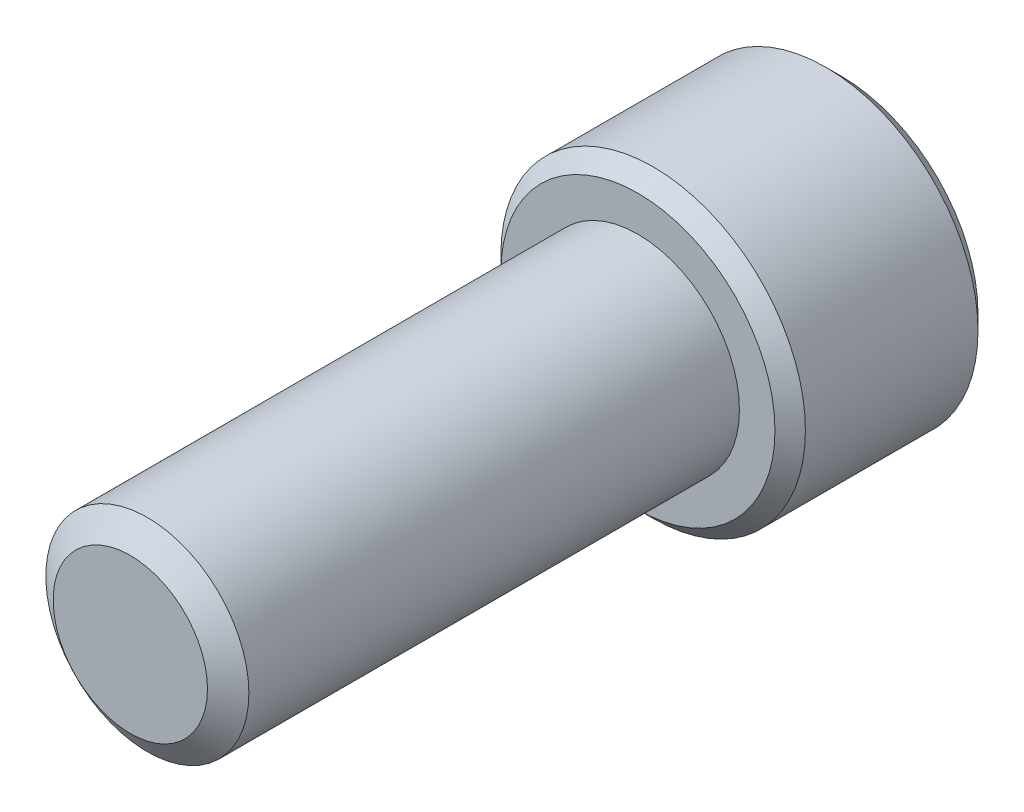
SolidWorks part; units mm, degrees
ref_plane "Front Plane" through (0, 0, 0) normal (0, 0, 1) x (1, 0, 0)
ref_plane "Top Plane" through (0, 0, 0) normal (0, 1, 0) x (1, 0, 0)
ref_plane "Right Plane" through (0, 0, 0) normal (1, 0, 0) x (0, 0, -1)
sketch "Sketch1" plane through (0, 0, 0) normal (0, 0, 1) x (1, 0, 0)
  circle A0 centre (0, 0) radius 6.35
  dimension "OD" = 12.7
extrude "Extrude1" add sketch "Sketch1" against normal blind 31.75
sketch "Sketch2" plane through (0, 0, 0) normal (0, 0, 1) x (1, 0, 0)
  circle A0 centre (0, 0) radius 6.35 construction
  circle A1 centre (0, 0) radius 6.35
curve "Helix/Spiral1" pitch 1.9538 height 33.7038 turns 17.25 parameters "pitch"=1.9538
sketch "Sketch3" plane through (0, 0, 0) normal (1, 0, 0) x (0, 0, -1)
  line L0 (-1.7096, 6.35) -> (-0.9769, 5.0809)
  line L1 (-0.9769, 5.0809) -> (-0.7327, 5.0809)
  line L2 (-0.7327, 5.0809) -> (0, 6.35)
  line L3 (-1.7096, 6.35) -> (0, 6.35)
  line L4 (-0.8548, 6.35) -> (-0.8548, 5.0809) construction
  line L5 (-1.3433, 5.7155) -> (-0.3663, 5.7155) construction
  line L6 (0, 6.35) -> (0, -6.35) construction
  dimension "D1" = 0.2442
  dimension "D2" = 0.9769
  dimension "D3" = 60
sketch "Sketch4" plane through (0, 0, 0) normal (1, 0, 0) x (0, 0, -1)
  line L0 (1.0665, 6.35) -> (0, 4.8269)
  line L1 (0, 4.8269) -> (0, 6.35)
  line L2 (1.0665, 6.35) -> (0, 6.35)
  line L3 (-1.7096, 6.35) -> (0, 6.35) construction
  line L4 (0, 0) -> (7.0209, 0) construction
  dimension "D1" = 55
  dimension "D2" = 0.254
revolve "Cut-Revolve1" cut sketch "Sketch4" angle 360 about L4
sketch "Sketch6" plane through (0, 0, -31.75) normal (0, 0, -1) x (-1, 0, 0)
  circle A0 centre (0, 0) radius 9.525
  dimension "head dia" = 19.05
extrude "Extrude2" add sketch "Sketch6" along normal blind 12.7
sketch "Sketch7" plane through (0, 0, -44.45) normal (0, 0, -1) x (-1, 0, 0)
  line L1 (0, 5.4993) -> (-4.7625, 2.7496)
  line L2 (-4.7625, 2.7496) -> (-4.7625, -2.7496)
  line L3 (-4.7625, -2.7496) -> (0, -5.4993)
  line L4 (0, -5.4993) -> (4.7625, -2.7496)
  line L5 (4.7625, -2.7496) -> (4.7625, 2.7496)
  line L6 (4.7625, 2.7496) -> (0, 5.4993)
  circle A0 centre (0, 0) radius 4.7625 construction
  dimension "hex dia" = 9.525
extrude "Cut-Extrude1" cut sketch "Sketch7" against normal blind 7.1438
sketch "Sketch8" plane through (0, 0, -44.45) normal (0, 0, -1) x (-1, 0, 0)
  circle A0 centre (0, 0) radius 5.4993
extrude "Cut-Extrude2" cut sketch "Sketch8" against normal through all draft 45
chamfer "Chamfer1" distance 0.9525 angle 45 2 edges at (-9.525, 0, -44.45) (-9.525, 0, -31.75)
sketch "Sketch9" plane through (0, 0, 0) normal (1, 0, 0) x (0, 0, -1)
  line L0 (0, 6.35) -> (0, -6.35) construction
  line L1 (20.5154, 6.35) -> (20.5154, -6.35) construction
  dimension "D1" = 20.5154
equation "\"D3@Helix/Spiral1\" = \"screw length@Extrude1\"+\"pitch@Helix/Spiral1\""
equation "\"D1@Sketch3\" = \"pitch@Helix/Spiral1\"*.125"
equation "\"D2@Sketch3\" = \"pitch@Helix/Spiral1\"*.5"
equation "\"D1@Cut-Extrude1\" = \"hex dia@Sketch7\"*.75"
equation "\"D1@Chamfer1\" = \"head dia@Sketch6\"*.05"
equation "\"D1@Sketch9\" = \"pitch@Helix/Spiral1\"*10.5"
